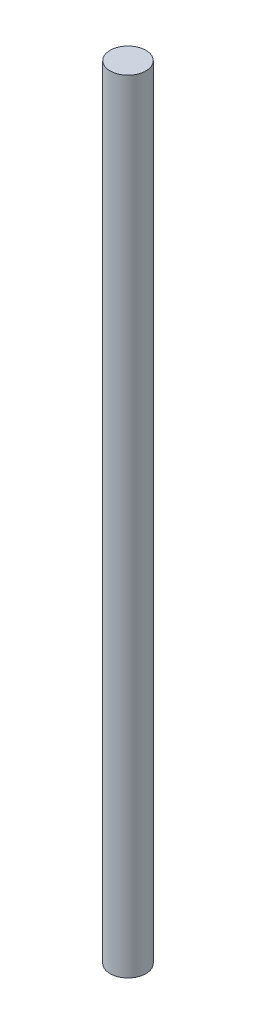
SolidWorks part; units mm, degrees
material "AISI 1020"
ref_plane "Plano frontal" through (0, 0, 0) normal (0, 0, 1) x (1, 0, 0)
ref_plane "Plano superior" through (0, 0, 0) normal (0, 1, 0) x (1, 0, 0)
ref_plane "Plano direito" through (0, 0, 0) normal (1, 0, 0) x (0, 0, -1)
sketch "Esboço1" plane through (0, 0, 0) normal (0, 1, 0) x (1, 0, 0)
  circle A0 centre (0, 0) radius 4
  dimension "D1" = 8
extrude "Ressalto-extrusão1" add sketch "Esboço1" along normal blind 175
sketch "Esboço2" plane through (0, 0, 0) normal (0, 0, 1) x (1, 0, 0)
  line L0 (0, 175) -> (0, 0) construction
  line L1 (4, 175) -> (-4, 175) construction
  point P5 (0, 87.5)
ref_plane "Plano1" through (0, 87.5, 0) normal (0, -1, 0) x (-1, 0, 0)
